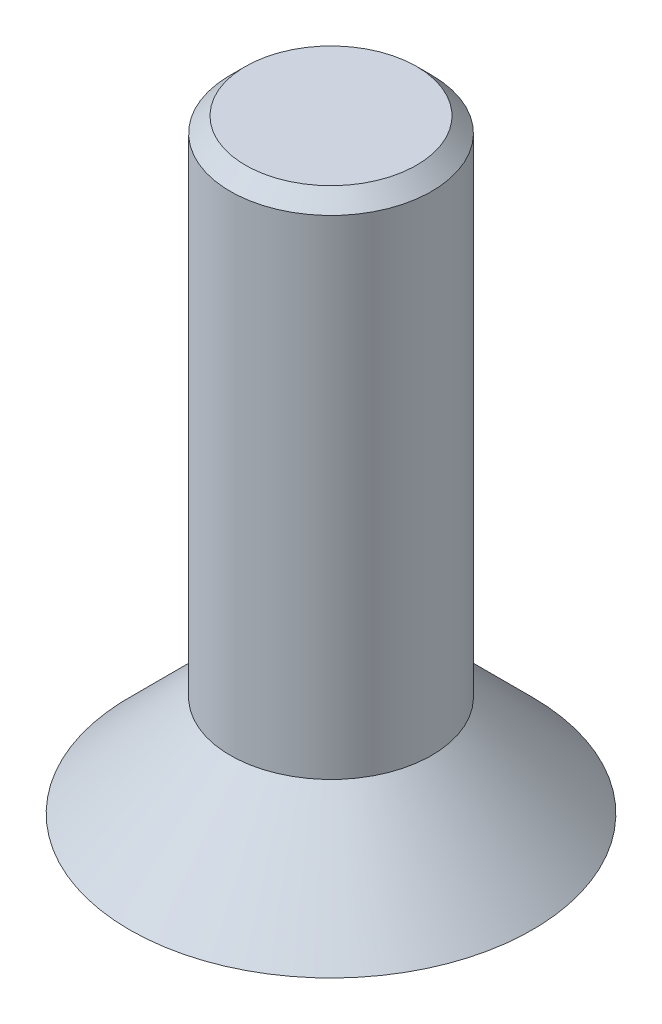
SolidWorks part; units mm, degrees
ref_plane "前视基准面" through (0, 0, 0) normal (0, 0, 1) x (1, 0, 0)
ref_plane "上视基准面" through (0, 0, 0) normal (0, 1, 0) x (1, 0, 0)
ref_plane "右视基准面" through (0, 0, 0) normal (1, 0, 0) x (0, 0, -1)
other "Configuration Table"
sketch "轴向轮廓" plane through (0, 0, 0) normal (0, 0, 1) x (1, 0, 0)
  line L0 (0, 0) -> (4, 0)
  line L1 (4, 0) -> (2, 2)
  line L2 (2, 2) -> (2, 11.7)
  line L3 (2, 11.7) -> (1.7, 12)
  line L4 (1.7, 12) -> (0, 12)
  line L5 (0, 12) -> (0, 0)
  line L6 (0, -2) -> (0, 14) construction
revolve "螺钉外形_旋转" add sketch "轴向轮廓" angle 360 about L6
sketch "内六角轮廓" plane through (0, 0, 0) normal (0, -1, 0) x (1, 0, 0)
  line L0 (1.4434, 0) -> (0.7217, 1.25)
  line L1 (0.7217, 1.25) -> (-0.7217, 1.25)
  line L2 (-0.7217, 1.25) -> (-1.4434, 0)
  line L3 (-1.4434, 0) -> (-0.7217, -1.25)
  line L4 (-0.7217, -1.25) -> (0.7217, -1.25)
  line L5 (0.7217, -1.25) -> (1.4434, 0)
extrude "内六角" cut sketch "内六角轮廓" against normal blind 1.5
